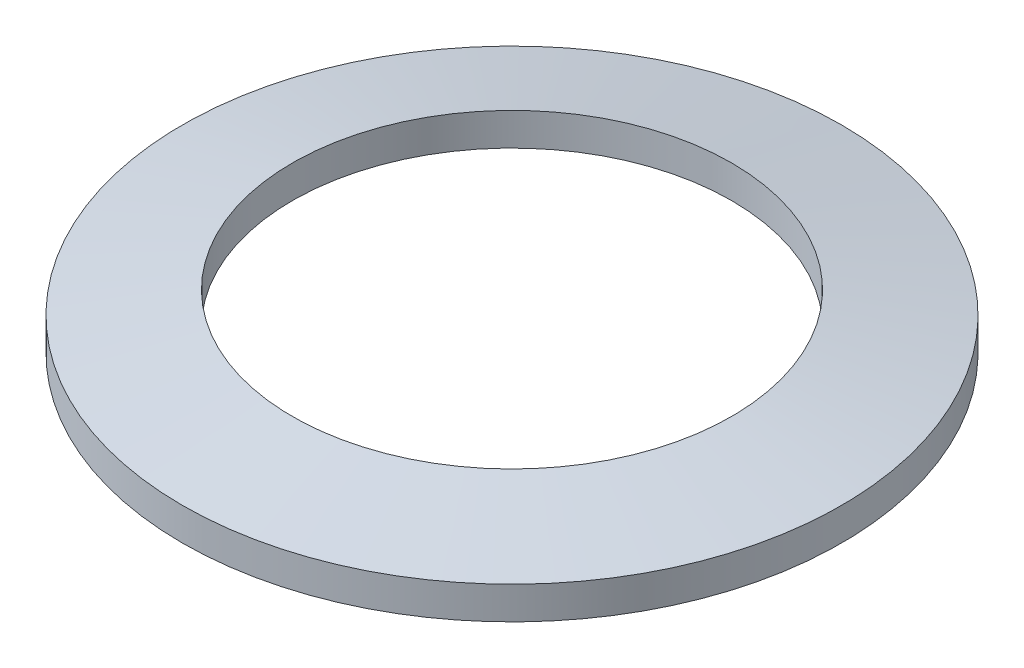
SolidWorks part; units mm, degrees
ref_plane "Front Plane" through (0, 0, 0) normal (0, 0, 1) x (1, 0, 0)
ref_plane "Top Plane" through (0, 0, 0) normal (0, 1, 0) x (1, 0, 0)
ref_plane "Right Plane" through (0, 0, 0) normal (1, 0, 0) x (0, 0, -1)
sketch "Sketch1" plane through (0, 0, 0) normal (0, 0, 1) x (1, 0, 0)
  line L0 (-14.9987, 0) -> (14.9987, 0) construction
  line L1 (-14.9987, 0) -> (-9.9949, 1.0035)
  line L2 (-9.9949, 1.0035) -> (-9.9949, 2.4892)
  line L3 (-9.9949, 2.4892) -> (-14.9987, 1.4857)
  line L4 (-14.9987, 1.4857) -> (-14.9987, 0)
  line L5 (0, 0) -> (0, 2.4892) construction
  line L6 (14.9987, 1.4857) -> (14.9987, 0) construction
  line L7 (9.9949, 2.4892) -> (14.9987, 1.4857) construction
  line L8 (9.9949, 1.0035) -> (9.9949, 2.4892) construction
  line L9 (14.9987, 0) -> (9.9949, 1.0035) construction
  dimension "D1" = 2.4892
  dimension "D2" = 1.4567
  dimension "D3" = 29.9974
  dimension "D4" = 19.9898
revolve "Revolve1" add sketch "Sketch1" angle 360 about L5
